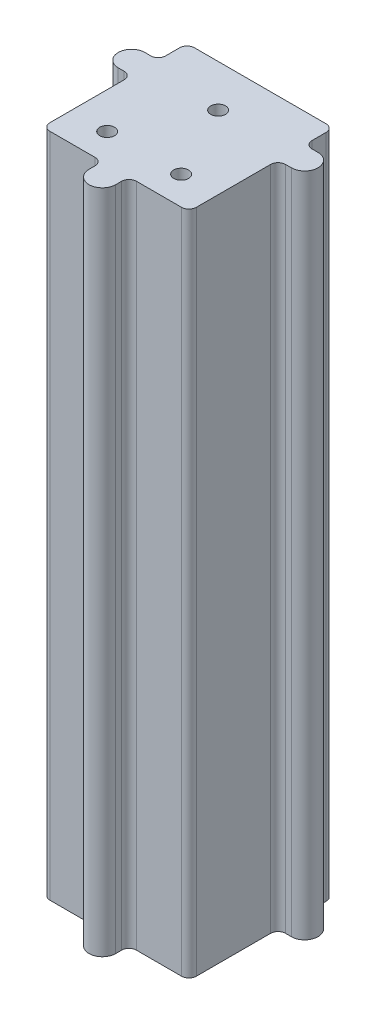
SolidWorks part; units mm, degrees
ref_plane "Front Plane" through (0, 0, 0) normal (0, 0, 1) x (1, 0, 0)
ref_plane "Top Plane" through (0, 0, 0) normal (0, 1, 0) x (1, 0, 0)
ref_plane "Right Plane" through (0, 0, 0) normal (1, 0, 0) x (0, 0, -1)
sketch "Sketch1" plane through (0, 0, 0) normal (0, -1, 0) x (1, 0, 0)
  line L0 (-19.8, 7.145) -> (-19.8, -9.145) construction
  line L6 (0, 14.945) -> (-23.4, 14.945) construction
  line L7 (-19.8, 7.145) -> (-19.8, 14.945) construction
  line L9 (-17.8, -24.145) -> (-3.6, -24.145)
  line L11 (0, 18.545) -> (0, -24.145) construction
  line L12 (-23.4, -2.8) -> (23.4, -2.8) construction
  line L13 (0, 14.945) -> (23.4, 14.945) construction
  line L14 (20, 22.2) -> (-20, 22.2) construction
  line L15 (-20, -27.8) -> (20, -27.8) construction
  line L17 (3.6, -24.145) -> (17.8, -24.145)
  line L23 (19.8, 12.945) -> (19.8, -7.145)
  line L24 (19.8, 7.145) -> (19.8, -24.145) construction
  line L25 (-23.4, -16.345) -> (-21.8, -16.345)
  line L26 (-23.4, -9.145) -> (-21.8, -9.145)
  line L27 (-19.8, -7.145) -> (-19.8, 12.945)
  line L28 (-17.8, 14.945) -> (-5.6, 14.945)
  line L29 (-3.6, 16.945) -> (-3.6, 18.545)
  line L30 (3.6, 18.545) -> (3.6, 16.945)
  line L31 (5.6, 14.945) -> (17.8, 14.945)
  line L32 (21.8, -9.145) -> (23.4, -9.145)
  line L33 (23.4, -16.345) -> (21.8, -16.345)
  line L34 (19.8, -18.345) -> (19.8, -22.145)
  line L35 (3.6, -24.145) -> (-3.6, -24.145)
  line L36 (-19.8, -18.345) -> (-19.8, -22.145)
  arc A0 (3.6, 18.545) -> (-3.6, 18.545) centre (0, 18.545) ccw
  arc A1 (-23.4, -9.145) -> (-23.4, -16.345) centre (-23.4, -12.745) ccw
  arc A3 (23.4, -9.145) -> (23.4, -16.345) centre (23.4, -12.745) cw
  arc A4 (-17.8, -24.145) -> (-19.8, -22.145) centre (-17.8, -22.145) cw
  arc A5 (-21.8, -16.345) -> (-19.8, -18.345) centre (-21.8, -18.345) cw
  arc A6 (19.8, -18.345) -> (21.8, -16.345) centre (21.8, -18.345) cw
  arc A7 (17.8, -24.145) -> (19.8, -22.145) centre (17.8, -22.145) ccw
  arc A8 (-21.8, -9.145) -> (-19.8, -7.145) centre (-21.8, -7.145) ccw
  arc A9 (21.8, -9.145) -> (19.8, -7.145) centre (21.8, -7.145) cw
  arc A10 (5.6, 14.945) -> (3.6, 16.945) centre (5.6, 16.945) cw
  arc A11 (-5.6, 14.945) -> (-3.6, 16.945) centre (-5.6, 16.945) ccw
  arc A12 (-19.8, 12.945) -> (-17.8, 14.945) centre (-17.8, 12.945) cw
  arc A13 (19.8, 12.945) -> (17.8, 14.945) centre (17.8, 12.945) ccw
  point P27 (-23.4, -24.145)
  point P29 (-19.8, -16.345)
  point P30 (23.4, -24.145)
  point P33 (23.4, 18.545)
  point P36 (-23.4, 18.545)
  point P39 (19.8, -16.345)
  point P47 (0, -2.8)
  point P56 (19.8, -9.145)
  point P59 (3.6, 14.945)
  point P62 (-3.6, 14.945)
  dimension "D1" = 3.6
  dimension "D2" = 3.6
  dimension "D3" = 3.6
  dimension "D9" = 2
  dimension "D4" = 2
  dimension "D5" = 2
  dimension "D8" = 2
  dimension "D6" = 46.8
  dimension "D7" = 11.4
  dimension "D10" = 31.29
  dimension "D11" = 46.8
  dimension "D13" = 3.655
extrude "Boss-Extrude1" add sketch "Sketch1" against normal blind 180
sketch "Sketch12" plane through (0, 0, 0) normal (0, -1, 0) x (1, 0, 0)
  circle A0 centre (0, 18.545) radius 1.55
  circle A1 centre (-23.4, -12.745) radius 1.55
  circle A2 centre (23.4, -12.745) radius 1.55
  dimension "D1" = 3.1
  dimension "D2" = 3.1
  dimension "D3" = 3.1
extrude "Cut-Extrude1" cut sketch "Sketch12" against normal blind 20
sketch "Sketch13" plane through (0, 180, 0) normal (0, 1, 0) x (1, 0, 0)
  line L0 (-23.4, 12.745) -> (24.3873, 12.745) construction
  line L1 (0, 0) -> (0, 12.745) construction
  line L2 (0, 12.745) -> (0, -7.255) construction
  line L3 (10, 12.745) -> (10, -7.255) construction
  circle A0 centre (0, 12.745) radius 2
  circle A1 centre (10, -7.255) radius 2
  circle A2 centre (-10, -7.255) radius 2
  point P13 (0, 0)
  dimension "D1" = 4
  dimension "D4" = 4
  dimension "D2" = 20
  dimension "D3" = 10
  dimension "D5" = 20
extrude "Cut-Extrude2" cut sketch "Sketch13" against normal blind 20
ref_plane "Plane1" through (0, 10, 0) normal (0, -1, 0) x (-1, 0, 0)
sketch "Sketch8" plane through (0, 10, 0) normal (0, -1, 0) x (-1, 0, 0)
  line L1 (0, 0.7793) -> (1.75, 1.7896)
  line L2 (1.75, 1.7896) -> (1.75, 3.8104)
  line L3 (1.75, 3.8104) -> (0, 4.8207)
  line L4 (0, 4.8207) -> (-1.75, 3.8104)
  line L5 (-1.75, 3.8104) -> (-1.75, 1.7896)
  line L6 (-1.75, 1.7896) -> (0, 0.7793)
  circle A0 centre (0, 2.8) radius 1.75 construction
  dimension "D1" = 3.5
sketch "Sketch10" plane through (0, 10, 0) normal (0, -1, 0) x (-1, 0, 0)
  line L0 (23.4, 16.345) -> (23.4, 20.545)
  line L1 (23.4, 16.345) -> (23.4, 20.545)
  line L2 (19.8, 24.145) -> (3.6, 24.145)
  line L3 (19.8, 24.145) -> (3.6, 24.145)
  line L4 (-3.6, 24.145) -> (-19.8, 24.145)
  line L5 (-3.6, 24.145) -> (-19.8, 24.145)
  line L6 (-23.4, 20.545) -> (-23.4, 16.345)
  line L7 (-23.4, 20.545) -> (-23.4, 16.345)
  line L8 (-23.4, 9.145) -> (-23.4, -3.545)
  line L9 (-23.4, 9.145) -> (-23.4, -3.545)
  line L10 (-23.4, -10.745) -> (-23.4, -14.945)
  line L11 (-23.4, -10.745) -> (-23.4, -14.945)
  line L12 (-19.8, -18.545) -> (-3.6, -18.545)
  line L13 (-19.8, -18.545) -> (-3.6, -18.545)
  line L14 (3.6, -18.545) -> (19.8, -18.545)
  line L15 (3.6, -18.545) -> (19.8, -18.545)
  line L16 (23.4, -14.945) -> (23.4, -10.745)
  line L17 (23.4, -14.945) -> (23.4, -10.745)
  line L18 (23.4, -3.545) -> (23.4, 9.145)
  line L19 (23.4, -3.545) -> (23.4, 9.145)
  arc A0 (23.4, 16.345) -> (23.4, 9.145) centre (23.4, 12.745) ccw
  arc A1 (23.4, 16.345) -> (23.4, 9.145) centre (23.4, 12.745) ccw
  arc A2 (23.4, 20.545) -> (19.8, 24.145) centre (19.8, 20.545) ccw
  arc A3 (23.4, 20.545) -> (19.8, 24.145) centre (19.8, 20.545) ccw
  arc A4 (-3.6, 24.145) -> (3.6, 24.145) centre (0, 24.145) ccw
  arc A5 (-3.6, 24.145) -> (3.6, 24.145) centre (0, 24.145) ccw
  arc A6 (-19.8, 24.145) -> (-23.4, 20.545) centre (-19.8, 20.545) ccw
  arc A7 (-19.8, 24.145) -> (-23.4, 20.545) centre (-19.8, 20.545) ccw
  arc A8 (-23.4, 9.145) -> (-23.4, 16.345) centre (-23.4, 12.745) ccw
  arc A9 (-23.4, 9.145) -> (-23.4, 16.345) centre (-23.4, 12.745) ccw
  arc A10 (-23.4, -10.745) -> (-23.4, -3.545) centre (-23.4, -7.145) ccw
  arc A11 (-23.4, -10.745) -> (-23.4, -3.545) centre (-23.4, -7.145) ccw
  arc A12 (-23.4, -14.945) -> (-19.8, -18.545) centre (-19.8, -14.945) ccw
  arc A13 (-23.4, -14.945) -> (-19.8, -18.545) centre (-19.8, -14.945) ccw
  arc A14 (3.6, -18.545) -> (-3.6, -18.545) centre (0, -18.545) ccw
  arc A15 (3.6, -18.545) -> (-3.6, -18.545) centre (0, -18.545) ccw
  arc A16 (19.8, -18.545) -> (23.4, -14.945) centre (19.8, -14.945) ccw
  arc A17 (19.8, -18.545) -> (23.4, -14.945) centre (19.8, -14.945) ccw
  arc A18 (23.4, -3.545) -> (23.4, -10.745) centre (23.4, -7.145) ccw
  arc A19 (23.4, -3.545) -> (23.4, -10.745) centre (23.4, -7.145) ccw
